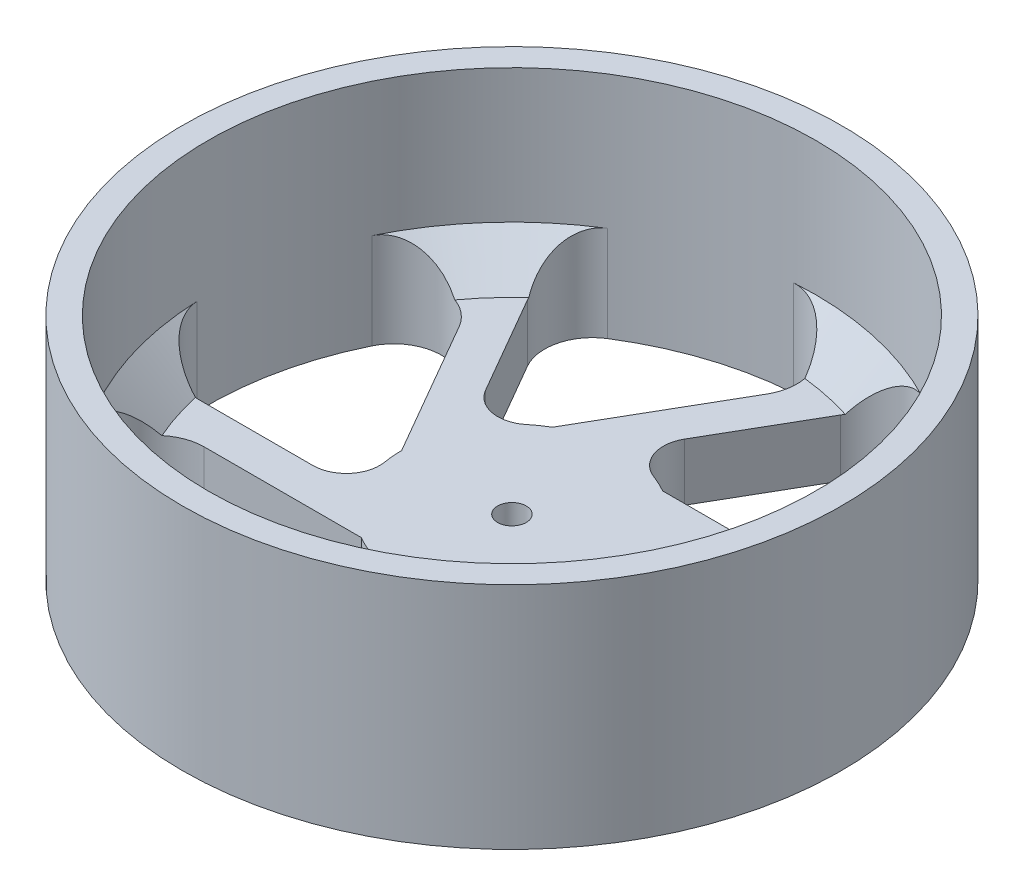
SolidWorks part; units mm, degrees
ref_plane "Front Plane" through (0, 0, 0) normal (0, 0, 1) x (1, 0, 0)
ref_plane "Top Plane" through (0, 0, 0) normal (0, 1, 0) x (1, 0, 0)
ref_plane "Right Plane" through (0, 0, 0) normal (1, 0, 0) x (0, 0, -1)
sketch "Sketch1" plane through (0, 0, 0) normal (0, 1, 0) x (1, 0, 0)
  circle A0 centre (0, 0) radius 34.5
  dimension "D1" = 69
extrude "Boss-Extrude1" add sketch "Sketch1" along normal blind 24
sketch "Sketch3" plane through (0, 0, 0) normal (0, 1, 0) x (1, 0, 0)
  line L0 (5.7735, 10) -> (30.1868, 10)
  line L1 (3.4641, 6) -> (-3.4641, 6) construction
  line L2 (-3.4641, 6) -> (-6.9282, 0) construction
  line L4 (-6.9282, 0) -> (-3.4641, -6) construction
  line L5 (-3.4641, -6) -> (3.4641, -6) construction
  line L6 (3.4641, -6) -> (6.9282, 0) construction
  line L7 (6.9282, 0) -> (3.4641, 6) construction
  line L9 (-6.9282, 0) -> (10.4183, 30.045)
  line L11 (5.7735, 10) -> (-5.7735, 10) construction
  line L12 (-5.7735, 10) -> (-11.547, 0) construction
  line L13 (-11.547, 0) -> (-5.7735, -10) construction
  line L14 (-5.7735, -10) -> (5.7735, -10) construction
  line L15 (5.7735, -10) -> (11.547, 0) construction
  line L16 (11.547, 0) -> (5.7735, 10) construction
  circle A0 centre (0, 0) radius 31.8
  circle A10 centre (0, 0) radius 6 construction
  circle A11 centre (0, 0) radius 10 construction
  circle A12 centre (0, 0) radius 34.5 construction
  circle A22 centre (0, 0) radius 34.5 construction
  arc A23 (14.8613, 28.1137) -> (8.1945, 26.1933) centre (12.5246, 23.6933) ccw
  arc A28 (22.209, 10) -> (26.3525, 17.7985) centre (22.209, 15) ccw
  circle A29 centre (0, 0) radius 11.547
  arc A30 (2.2228, 15.85) -> (4.0318, 10.8203) centre (5.2539, 14.1) ccw
  point P6 (0, 0)
  dimension "D1" = 3.5
  dimension "D2" = 4
  dimension "D3" = 12
  dimension "D4" = 2.7
  dimension "D5" = 10
sketch "Sketch6" plane through (0, 0, 0) normal (0, 1, 0) x (1, 0, 0)
  circle A0 centre (0, 0) radius 1.5
  dimension "D1" = 3
extrude "Cut-Extrude6" cut sketch "Sketch6" along normal up to surface (24 mm away) up to face at (0, 24, 34.5)
ref_plane "Plane1" through (0, 12, 0) normal (0, 1, 0) x (1, 0, 0)
extrude "Cut-Extrude7" cut sketch "Sketch3" along normal up to surface (24 mm away)
pattern_circular "CirPattern1" count 6 over 360 about axis through (0, 0, 0) along (0, 1, 0) of "Cut-Extrude7"
sketch "Sketch8" plane through (0, 12, 0) normal (0, 1, 0) x (1, 0, 0)
  line L0 (0, 0) -> (0, -34.5) construction
  line L5 (-4.4052, -32.2001) -> (4.4052, -32.2001)
  line L6 (-2.5, -35.5) -> (2.5, -35.5)
  line L7 (4.4052, -32.2001) -> (2.5, -35.5)
  line L8 (-4.4052, -32.2001) -> (-2.5, -35.5)
  circle A7 centre (0, 0) radius 32.5 construction
  circle A8 centre (0, 0) radius 34.5 construction
  point P10 (0, -32.2001)
  point P13 (0, -35.5)
  dimension "D1" = 2
  dimension "D2" = 1
  dimension "D3" = 60
  dimension "D4" = 5
sketch "Sketch13" [suppressed] plane through (0, 24, 0) normal (0, 1, 0) x (0.9417, 0, -0.3365)
  line L0 (0, 0) -> (0, -34.5) construction
  line L5 (-4.4052, -32.2001) -> (4.4052, -32.2001)
  line L6 (-2.5, -35.5) -> (2.5, -35.5)
  line L7 (4.4052, -32.2001) -> (2.5, -35.5)
  line L8 (-4.4052, -32.2001) -> (-2.5, -35.5)
  circle A7 centre (0, 0) radius 32.5 construction
  point P10 (0, -32.2001)
  point P13 (0, -35.5)
loft "Cut-Loft6" [suppressed] cut profiles "Sketch13", "Sketch8"
mirror "Mirror10" [suppressed] about plane through (0, 12, 0) normal (0, 1, 0)
pattern_circular "CirPattern6" [suppressed] count 6 over 360
sketch "Sketch14" plane through (0, 0, 0) normal (0, 0, 1) x (1, 0, 0)
  line L1 (34.5, 0) -> (34.5, 24) construction
  line L2 (32, 13) -> (32, 12)
  line L3 (37.95, 12) -> (-37.95, 12) construction
  line L4 (32, 12) -> (34.5, 12)
  line L5 (32, 13) -> (34.5, 14)
  line L6 (34.5, 14) -> (34.5, 12)
  dimension "D1" = 2.5
  dimension "D2" = 2
  dimension "D3" = 1
revolve "Revolve1" add sketch "Sketch14" angle 360 about axis through (0, 24, 0) along (0, -1, 0)
mirror "Mirror11" about plane through (0, 12, 0) normal (0, 1, 0) of "Revolve1"
sketch "Sketch15" plane through (0, 0, 0) normal (0, 0, 1) x (1, 0, 0)
  line L0 (1.5, 6) -> (1.5, 0)
  line L1 (1.5, 6) -> (27.8, 6)
  line L2 (-34.5, 0) -> (34.5, 0) construction
  line L3 (31.8, 10) -> (31.8, 24)
  line L4 (34.5, 24) -> (-34.5, 24) construction
  line L5 (31.8, 24) -> (0, 24)
  line L6 (0, 0) -> (0, 34.2011) construction
  line L7 (0, 24) -> (0, 0) construction
  line L8 (1.5, 0) -> (0, 0)
  line L9 (0, 6) -> (0, 0)
  line L11 (34.5, 0) -> (34.5, 24) construction
  line L13 (31.8, 10) -> (27.8, 6)
  line L14 (0, 6) -> (0, 0) construction
  line L16 (0, 24) -> (0, 0) construction
  line L19 (0, 6) -> (0, 24)
  point P21 (31.8, 9.9219)
  dimension "D1" = 6
  dimension "D2" = 2.7
  dimension "D3" = 6.7
  dimension "D4" = 1.5
  dimension "D5" = 45
revolve "Cut-Revolve5" cut sketch "Sketch15" angle 360 about L14
sketch "Sketch16" plane through (0, 0, 0) normal (0, 1, 0) x (1, 0, 0)
  line L1 (0, 6.9398) -> (-6.01, 3.4699)
  line L2 (-6.01, 3.4699) -> (-6.01, -3.4699)
  line L3 (-6.01, -3.4699) -> (0, -6.9398)
  line L4 (0, -6.9398) -> (6.01, -3.4699)
  line L5 (6.01, -3.4699) -> (6.01, 3.4699)
  line L6 (6.01, 3.4699) -> (0, 6.9398)
  circle A0 centre (0, 0) radius 6.01 construction
  dimension "D1" = 12.02
extrude "Cut-Extrude8" [suppressed] cut sketch "Sketch16" along normal blind 9
sketch "Sketch17" plane through (0, 0, 0) normal (0, 1, 0) x (1, 0, 0)
  circle A0 centre (0, 0) radius 8 construction
  circle A1 centre (0, 8) radius 1.5
  circle A2 centre (8, 0) radius 1.5
  circle A3 centre (0, -8) radius 1.5
  circle A4 centre (-8, 0) radius 1.5
  point P14 (0, 0)
  dimension "D1" = 16
  dimension "D2" = 3
  dimension "D3" = 4
extrude "Cut-Extrude9" [suppressed] cut sketch "Sketch17" along normal up to surface (8 mm away)
sketch "Sketch18" [suppressed] plane through (0, 0, 0) normal (0, 1, 0) x (1, 0, 0)
  line L0 (-3.0808, -3.8007) -> (3.0808, 3.8007) construction
  line L1 (-4.093, -5.0495) -> (4.093, 5.0495) construction
  circle A1 centre (3.0808, 3.8007) radius 1.6075
  circle A2 centre (-3.0808, -3.8007) radius 1.6075
  circle A3 centre (0, 0) radius 5 construction
  point P3 (0, 0)
  point P5 (1.74, 4.6875)
  point P6 (4.2259, 2.6725)
  point P11 (0, 0)
  dimension "D2" = 3.2
  dimension "D1" = 13
extrude "Cut-Extrude10" [suppressed] cut sketch "Sketch18" against normal up to surface (12 mm away)
